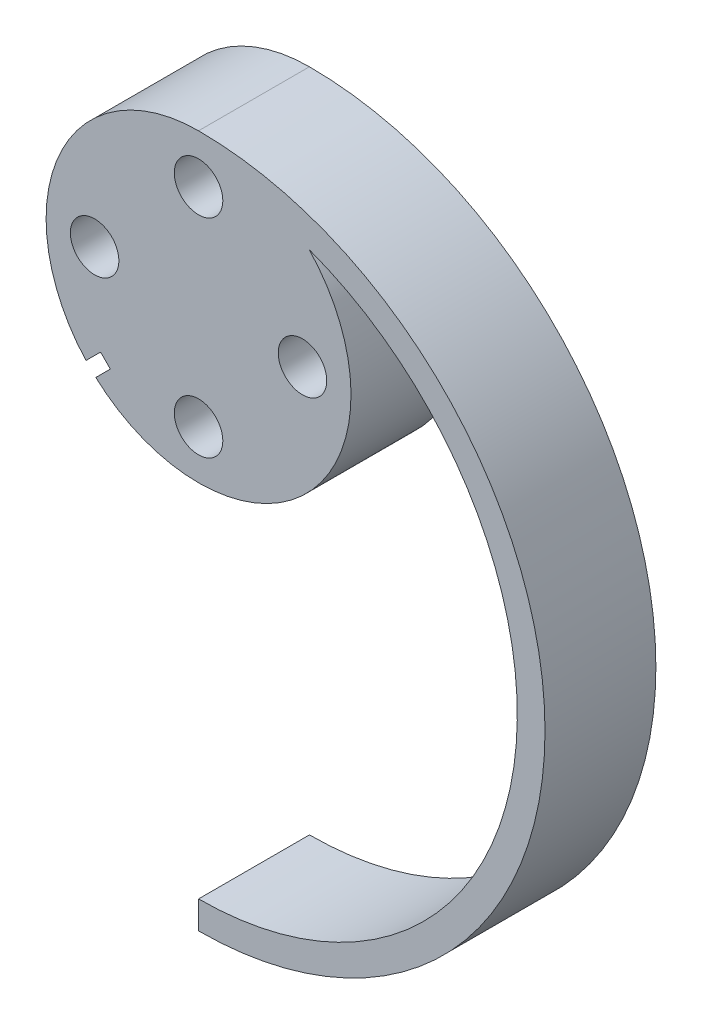
SolidWorks part; units mm, degrees
ref_plane "Front Plane" through (0, 0, 0) normal (0, 0, 1) x (1, 0, 0)
ref_plane "Top Plane" through (0, 0, 0) normal (0, 1, 0) x (1, 0, 0)
ref_plane "Right Plane" through (0, 0, 0) normal (1, 0, 0) x (0, 0, -1)
sketch "Sketch1" plane through (0, 0, 0) normal (0, 0, 1) x (1, 0, 0)
  line L0 (0, 0) -> (0, -39) construction
  line L1 (0, -39) -> (0, -37)
  circle A0 centre (0, 0) radius 11 construction
  circle A1 centre (0, 0) radius 7.5 construction
  circle A2 centre (0, 7.5) radius 1.75
  circle A3 centre (-7.5, 0) radius 1.75
  circle A4 centre (0, -7.5) radius 1.75
  circle A5 centre (7.5, 0) radius 1.75
  arc A6 (0, 11) -> (0, -11) centre (0, 0) ccw
  arc A7 (0, 11) -> (0, -39) centre (0, -14) cw
  arc A8 (7.9796, 7.5714) -> (0, -37) centre (0, -14) cw
  arc A9 (0, -11) -> (7.9796, 7.5714) centre (0, 0) ccw
  point P12 (0, 11)
  dimension "D1" = 22
  dimension "D2" = 15
  dimension "D3" = 3.5
  dimension "D4" = 2
  dimension "D5" = 50
extrude "Boss-Extrude1" add sketch "Sketch1" along normal blind 8
sketch "Sketch2" plane through (0, 0, 0) normal (0, 0, -1) x (-1, 0, 0)
  line L0 (0, 0) -> (7.7782, -7.7782) construction
  line L1 (0, 0) -> (0, -11) construction
  line L2 (9.1924, -8.4853) -> (7.0711, -6.364)
  line L3 (9.1924, -8.4853) -> (8.4853, -9.1924)
  line L4 (7.0711, -6.364) -> (6.364, -7.0711)
  line L5 (8.4853, -9.1924) -> (6.364, -7.0711)
  line L6 (9.1924, -8.4853) -> (6.364, -7.0711) construction
  line L7 (7.0711, -6.364) -> (8.4853, -9.1924) construction
  arc A0 (-7.9796, 7.5714) -> (0, 11) centre (0, 0) ccw construction
  dimension "D1" = 45
  dimension "D2" = 1
  dimension "D3" = 1.5
extrude "Cut-Extrude1" cut sketch "Sketch2" against normal through all both and the other way through all
